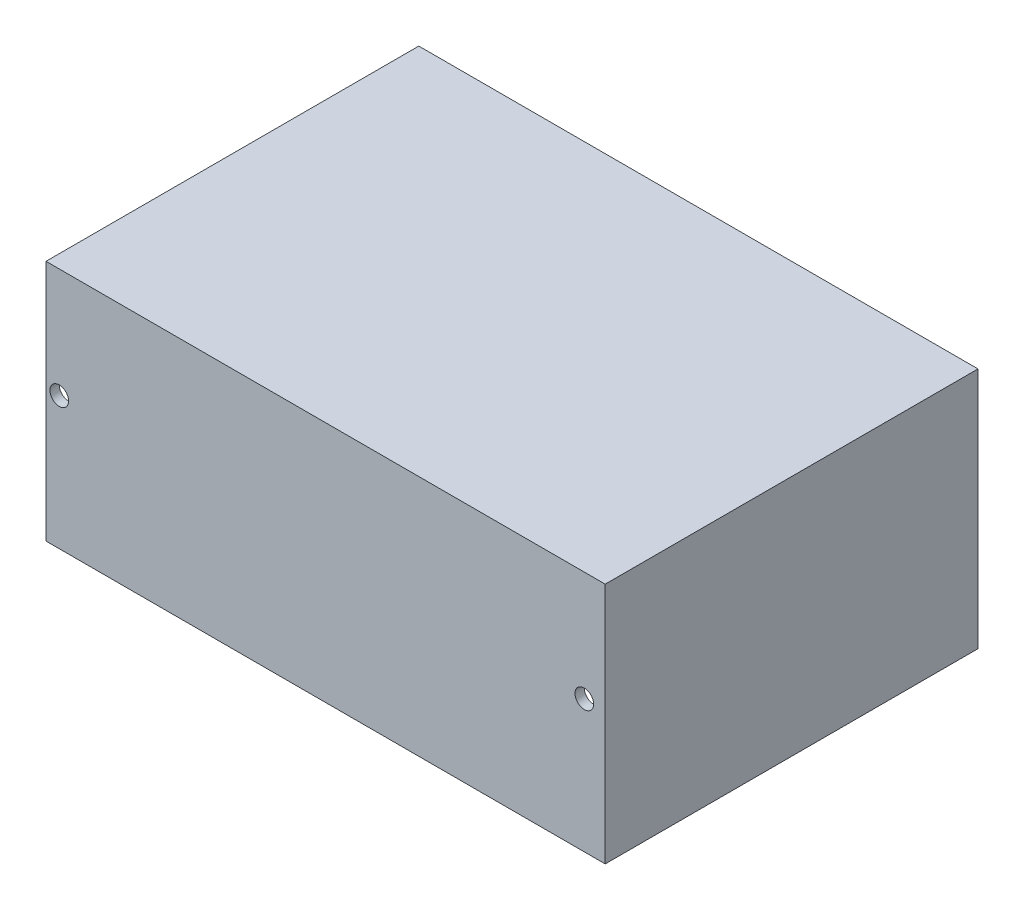
SolidWorks part; units mm, degrees
ref_plane "Front Plane" through (0, 0, 0) normal (0, 0, 1) x (1, 0, 0)
ref_plane "Top Plane" through (0, 0, 0) normal (0, 1, 0) x (1, 0, 0)
ref_plane "Right Plane" through (0, 0, 0) normal (1, 0, 0) x (0, 0, -1)
sketch "Sketch3" plane through (0, 0, 0) normal (1, 0, 0) x (0, 0, -1)
  line L1 (-181.1561, 123.885) -> (18.8439, 123.885)
  line L2 (-181.1561, 123.885) -> (-181.1561, -6.115)
  line L3 (-181.1561, -6.115) -> (18.8439, -6.115)
  line L4 (18.8439, 123.885) -> (18.8439, -6.115)
  dimension "D1" = 130
  dimension "D2" = 200
extrude "Boss-Extrude1" add sketch "Sketch3" along normal blind 300
shell "Shell2" thickness 5
sketch "Sketch12" plane through (0, 0, -18.8439) normal (0, 0, -1) x (-1, 0, 0)
  circle A0 centre (-288.795, 65) radius 5
  point P2 (0, 0)
  point P3 (0, 0)
  point P4 (0, 0)
  point P5 (0, 0)
  point P6 (0, 0)
  point P7 (0, 0)
  point P8 (0, 0)
  point P9 (0, 0)
  point P10 (0, 0)
  point P11 (0, 0)
  point P12 (0, 0)
extrude "Cut-Extrude1" cut sketch "Sketch12" against normal blind 300
sketch "Sketch13" plane through (0, 0, 181.1561) normal (0, 0, 1) x (1, 0, 0)
  circle A0 centre (7.1054, 65) radius 5
  point P2 (0, 0)
  point P3 (0, 0)
  point P4 (0, 0)
  point P5 (0, 0)
  point P6 (0, 0)
extrude "Cut-Extrude3" cut sketch "Sketch13" against normal blind 300
